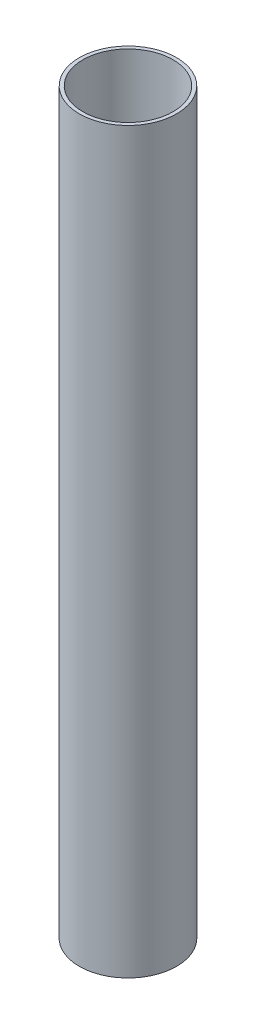
SolidWorks part; units mm, degrees
material "AISI 4340 Steel, normalized"
ref_plane "Front Plane" through (0, 0, 0) normal (0, 0, 1) x (1, 0, 0)
ref_plane "Top Plane" through (0, 0, 0) normal (0, 1, 0) x (1, 0, 0)
ref_plane "Right Plane" through (0, 0, 0) normal (1, 0, 0) x (0, 0, -1)
sketch "Sketch1" plane through (0, 0, 0) normal (0, 1, 0) x (1, 0, 0)
  circle A0 centre (0, 0) radius 20.5
  circle A1 centre (0, 0) radius 19
extrude "Boss-Extrude1" add sketch "Sketch1" along normal blind 311
